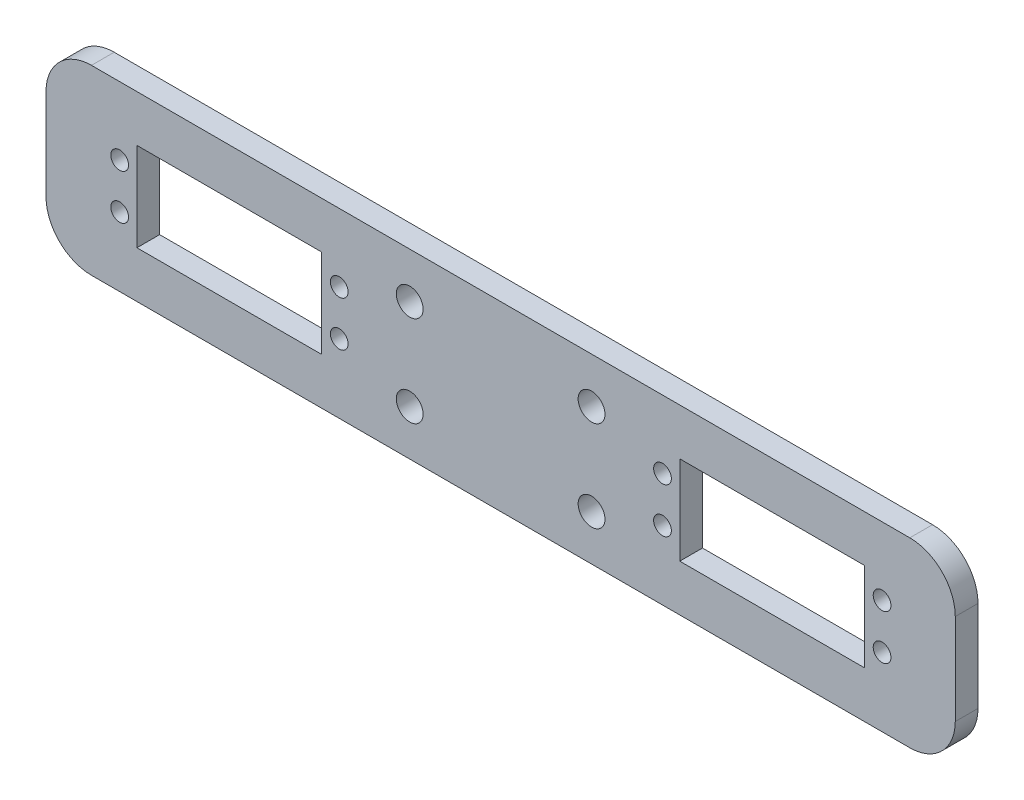
SolidWorks part; units mm, degrees
ref_plane "Alzado" through (0, 0, 0) normal (0, 0, 1) x (1, 0, 0)
ref_plane "Planta" through (0, 0, 0) normal (0, 1, 0) x (1, 0, 0)
ref_plane "Vista lateral" through (0, 0, 0) normal (1, 0, 0) x (0, 0, -1)
sketch "Croquis1" plane through (0, 0, 0) normal (0, 0, 1) x (1, 0, 0)
  line L0 (-25, -5) -> (162.963, -5) construction
  line L1 (-25, -5) -> (-25, 62.6248) construction
  line L2 (-125, -25) -> (-125, 15)
  line L3 (75, -25) -> (75, 15)
  line L4 (75, 15) -> (-125, 15)
  line L5 (75, -25) -> (-125, -25)
  dimension "D1" = 200
  dimension "D2" = 40
extrude "Extruir1" add sketch "Croquis1" along normal mid plane 5
fillet "Redondeo1" radius 10 4 edges at (-125, -25, 0) (75, -25, 0) (75, 15, 0) (-125, 15, 0)
sketch "Croquis3" plane through (0, 0, 2.5) normal (0, 0, 1) x (1, 0, 0)
  line L0 (55, -14.75) -> (14.4, -14.75)
  line L2 (-64.4, 4.75) -> (-64.4, -14.75)
  line L4 (0, 0) -> (0, 76.8537) construction
  line L5 (14.4, 4.75) -> (14.4, -14.75)
  line L6 (-105, -14.75) -> (-105, 4.75)
  line L7 (55, 4.75) -> (14.4, 4.75)
  line L8 (-105, 4.75) -> (-64.4, 4.75)
  line L9 (-105, -14.75) -> (-64.4, -14.75)
  line L10 (55, -14.75) -> (55, 4.75)
extrude "Extruir2" cut sketch "Croquis3" against normal blind 10
sketch "Croquis4" plane through (0, 0, 2.5) normal (0, 0, 1) x (1, 0, 0)
  circle A0 centre (58.9, -9.85) radius 1.95 construction
  circle A1 centre (58.9, -9.85) radius 1.95
  circle A2 centre (58.9, 0.05) radius 1.95 construction
  circle A3 centre (10.6, 0.05) radius 1.95 construction
  circle A4 centre (10.6, -9.85) radius 1.95 construction
  circle A5 centre (-108.8, -9.85) radius 1.95 construction
  circle A6 centre (-108.8, 0.05) radius 1.95 construction
  circle A7 centre (-60.5, 0.05) radius 1.95 construction
  circle A8 centre (-60.5, -9.85) radius 1.95 construction
  circle A9 centre (58.9, 0.05) radius 1.95
  circle A10 centre (10.6, 0.05) radius 1.95
  circle A11 centre (10.6, -9.85) radius 1.95
  circle A12 centre (-108.8, -9.85) radius 1.95
  circle A13 centre (-108.8, 0.05) radius 1.95
  circle A14 centre (-60.5, 0.05) radius 1.95
  circle A15 centre (-60.5, -9.85) radius 1.95
extrude "Cortar-Extruir1" cut sketch "Croquis4" against normal blind 10
sketch "Croquis5" plane through (0, 0, 2.5) normal (0, 0, 1) x (1, 0, 0)
  circle A1 centre (-45, 5) radius 2.95
  circle A2 centre (-45, -15) radius 2.95
  circle A3 centre (-5, -15) radius 2.95
  circle A4 centre (-5, 5) radius 2.95
extrude "Cortar-Extruir3" cut sketch "Croquis5" against normal blind 10
